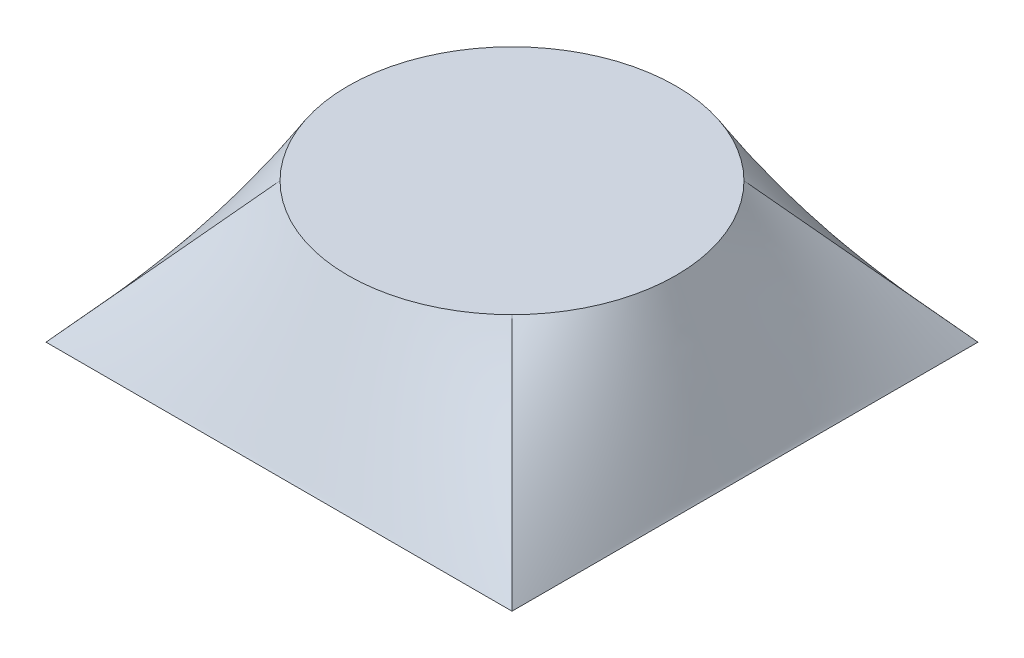
SolidWorks part; units mm, degrees
ref_plane "Front" through (0, 0, 0) normal (0, 0, 1) x (1, 0, 0)
ref_plane "Top" through (0, 0, 0) normal (0, 1, 0) x (1, 0, 0)
ref_plane "Right" through (0, 0, 0) normal (1, 0, 0) x (0, 0, -1)
sketch "Эскиз1" plane through (0, 0, 0) normal (0, 1, 0) x (1, 0, 0)
  line L1 (20, 20) -> (-20, 20)
  line L2 (20, 20) -> (20, -20)
  line L3 (20, -20) -> (-20, -20)
  line L4 (-20, 20) -> (-20, -20)
  line L5 (20, 20) -> (-20, -20) construction
  line L6 (20, -20) -> (-20, 20) construction
  point P0 (0, 0)
  dimension "D1" = 40
  dimension "D2" = 40
ref_plane "Плоскость1" through (0, 12, 0) normal (0, 1, 0) x (1, 0, 0)
sketch "Эскиз2" plane through (0, 12, 0) normal (0, 1, 0) x (1, 0, 0)
  circle A0 centre (0, 0) radius 14.08
loft "По сечениям1" add profiles "Эскиз1", "Эскиз2"
